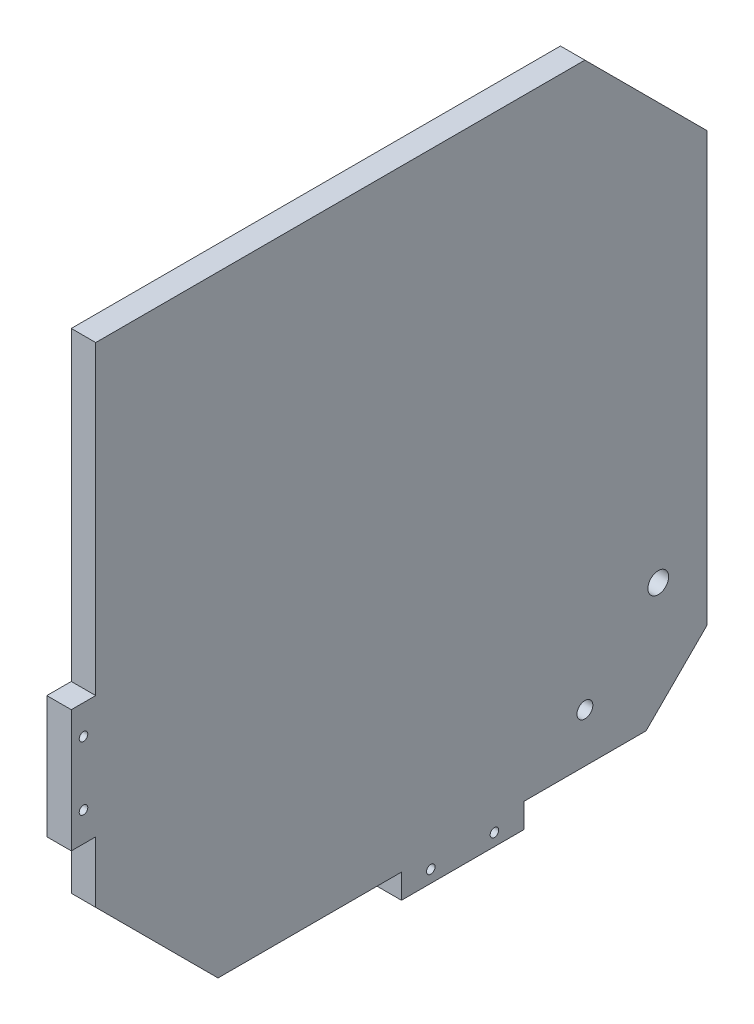
SolidWorks part; units mm, degrees
material "ABS PC"
ref_plane "Спереди" through (0, 0, 0) normal (0, 0, 1) x (1, 0, 0)
ref_plane "Сверху" through (0, 0, 0) normal (0, 1, 0) x (1, 0, 0)
ref_plane "Справа" through (0, 0, 0) normal (1, 0, 0) x (0, 0, -1)
sketch "Sketch1" plane through (0, 0, 0) normal (1, 0, 0) x (0, 0, -1)
  line L0 (50, 0) -> (125, 0)
  line L1 (0, 250) -> (200, 250)
  line L2 (200, 250) -> (250, 200)
  line L3 (250, 200) -> (250, 25)
  line L4 (125, 0) -> (125, -10)
  line L5 (125, -10) -> (175, -10)
  line L6 (175, -10) -> (175, 0)
  line L7 (175, 0) -> (225, 0)
  line L8 (0, 250) -> (0, 125)
  line L9 (0, 125) -> (-10, 125)
  line L10 (-10, 125) -> (-10, 75)
  line L11 (-10, 75) -> (0, 75)
  line L12 (0, 75) -> (0, 50)
  line L14 (200, 250) -> (250, 250) construction
  line L15 (250, 250) -> (250, 200) construction
  line L16 (250, 25) -> (250, 0) construction
  line L17 (250, 25) -> (225, 0)
  line L18 (0, 50) -> (50, 0)
  line L19 (250, 0) -> (225, 0) construction
  line L20 (0, 50) -> (0, 0) construction
  line L21 (0, 0) -> (50, 0) construction
  circle A0 centre (-5, 113) radius 1.75
  circle A1 centre (-5, 87) radius 1.75
  circle A2 centre (137, -5) radius 1.75
  circle A3 centre (163, -5) radius 1.75
  dimension "D13" = 3.5
  dimension "D16" = 5
  dimension "D17" = 12
  dimension "D18" = 12
  dimension "D19" = 5
  dimension "D1" = 250
  dimension "D2" = 250
  dimension "D3" = 50
  dimension "D4" = 50
  dimension "D5" = 50
  dimension "D6" = 50
  dimension "D7" = 50
  dimension "D8" = 25
  dimension "D9" = 25
  dimension "D10" = 10
  dimension "D11" = 75
  dimension "D12" = 75
  dimension "D14" = 12
  dimension "D15" = 12
extrude "Boss-Extrude1" add sketch "Sketch1" along normal blind 10
sketch "Sketch2" plane through (0, 225, -225) normal (0, 0.7071, -0.7071) x (1, 0, 0)
  line L1 (10, 35.3553) -> (10, -35.3553) construction
  line L2 (10, -35.3553) -> (0, -35.3553) construction
  circle A0 centre (5, 4.6447) radius 1.5
  circle A1 centre (5, -25.3553) radius 1.5
  dimension "D1" = 3
  dimension "D2" = 30
  dimension "D3" = 10
  dimension "D4" = 5
extrude "Cut-Extrude1" cut sketch "Sketch2" against normal blind 15
sketch "Sketch3" plane through (10, 0, 0) normal (1, 0, 0) x (0, 0, -1)
  line L0 (175, 0) -> (225, 0) construction
  line L1 (250, 25) -> (250, 200) construction
  circle A0 centre (230, 50) radius 4.25
  circle A1 centre (200, 20) radius 3.25
  dimension "D1" = 8.5
  dimension "D3" = 30
  dimension "D4" = 20
  dimension "D5" = 20
  dimension "D6" = 6.5
  dimension "D2" = 30
extrude "Cut-Extrude2" cut sketch "Sketch3" against normal through all
